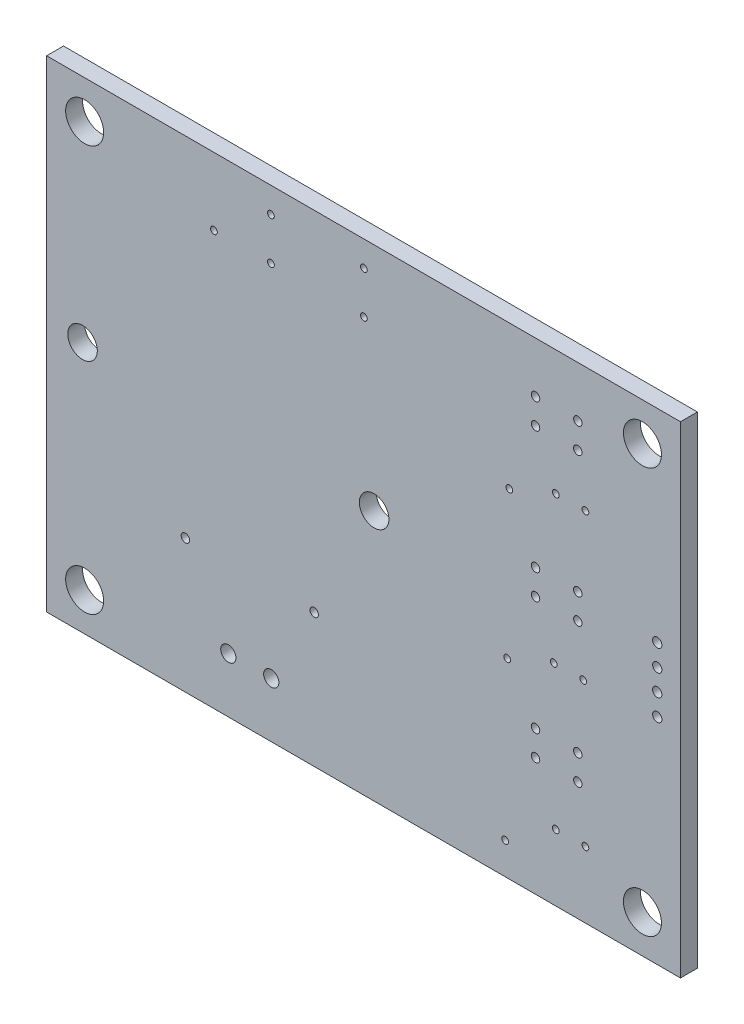
SolidWorks part; units mm, degrees
ref_plane "Спереди" through (0, 0, 0) normal (0, 0, 1) x (1, 0, 0)
ref_plane "Сверху" through (0, 0, 0) normal (0, 1, 0) x (1, 0, 0)
ref_plane "Справа" through (0, 0, 0) normal (1, 0, 0) x (0, 0, -1)
sketch "Эскиз1" plane through (0, 0, 0) normal (0, 0, 1) x (1, 0, 0)
  line L0 (-50.6905, 0) -> (50.2733, 0) construction
  line L1 (0, 39.9475) -> (0, -33.0636) construction
  line L2 (-16, -22) -> (-10.92, -22) construction
  line L3 (-37.5, -28.5) -> (37.5, -28.5)
  line L4 (-37.5, -28.5) -> (-37.5, 28.5)
  line L5 (-37.5, 28.5) -> (37.5, 28.5)
  line L6 (37.5, -28.5) -> (37.5, 28.5)
  line L7 (34.75, -3.12) -> (34.75, 2.3952) construction
  line L8 (-5.84, -12.7) -> (-33.6993, -12.7) construction
  circle A0 centre (-33, 24) radius 2.25
  circle A1 centre (33, 24) radius 2.25
  circle A2 centre (33, -24) radius 2.25
  circle A3 centre (-33, -24) radius 2.25
  circle A4 centre (-16, -22) radius 0.9
  circle A5 centre (-10.92, -22) radius 0.9
  circle A6 centre (34.75, -3.12) radius 0.55
  circle A7 centre (34.75, -0.58) radius 0.55
  circle A8 centre (34.75, 1.96) radius 0.55
  circle A9 centre (34.75, 4.5) radius 0.55
  circle A10 centre (-5.84, -12.7) radius 0.5
  circle A11 centre (-21.08, -12.7) radius 0.5
  circle A12 centre (-33.25, 1.25) radius 1.75
  circle A13 centre (1.25, 1.25) radius 1.75
  dimension "D3" = 4.5
  dimension "D5" = 4.5
  dimension "D8" = 1.8
  dimension "D9" = 5.08
  dimension "D10" = 1.1
  dimension "D13" = 2.54
  dimension "D14" = 2.54
  dimension "D15" = 2.54
  dimension "D16" = 1
  dimension "D20" = 3.5
  dimension "D23" = 38.75
  dimension "D24" = 29.75
  dimension "D1" = 75
  dimension "D2" = 57
  dimension "D4" = 4.5
  dimension "D6" = 6.5
  dimension "D7" = 21.5
  dimension "D11" = 72.25
  dimension "D12" = 25.38
  dimension "D17" = 15.8
  dimension "D18" = 31.66
  dimension "D19" = 16.42
  dimension "D21" = 4.25
  dimension "D22" = 29.75
extrude "Вытянуть1" add sketch "Эскиз1" along normal blind 2
sketch "Эскиз2" plane through (0, 0, 2) normal (0, 0, 1) x (1, 0, 0)
  line L0 (-37.5, -28.5) -> (37.5, -28.5) construction
  line L1 (-37.5, 28.5) -> (-37.5, -28.5) construction
  line L2 (-17.7, 20.5) -> (2.8598, 20.5) construction
  line L3 (19.3649, -20.65) -> (27.9828, -20.65) construction
  line L4 (19.3788, -3.72) -> (27.9967, -3.72) construction
  line L5 (19.4694, 13.75) -> (28.0873, 13.75) construction
  circle A0 centre (-17.7, 20.5) radius 0.4
  circle A1 centre (16.75, -24.75) radius 0.4
  circle A2 centre (17, -6) radius 0.4
  circle A3 centre (17.25, 11.5) radius 0.4
  circle A4 centre (-10.96, 20.5) radius 0.4
  circle A5 centre (0.04, 20.5) radius 0.4
  circle A6 centre (-10.96, 25.5) radius 0.4
  circle A7 centre (0.04, 25.5) radius 0.4
  circle A8 centre (22.75, -20.65) radius 0.4
  circle A9 centre (26.25, -20.65) radius 0.4
  circle A10 centre (22.5, -3.72) radius 0.4
  circle A11 centre (26, -3.72) radius 0.4
  circle A12 centre (22.75, 13.75) radius 0.4
  circle A13 centre (26.25, 13.75) radius 0.4
  dimension "D1" = 0.8
  dimension "D4" = 3.75
  dimension "D12" = 5
  dimension "D13" = 5
  dimension "D14" = 0.8
  dimension "D16" = 11
  dimension "D17" = 3.5
  dimension "D18" = 0.8
  dimension "D23" = 3.5
  dimension "D24" = 3.5
  dimension "D25" = 0.8
  dimension "D27" = 60.25
  dimension "D2" = 49
  dimension "D3" = 19.8
  dimension "D5" = 54.25
  dimension "D6" = 54.5
  dimension "D7" = 22.5
  dimension "D8" = 40
  dimension "D9" = 54.75
  dimension "D10" = 26.54
  dimension "D11" = 37.54
  dimension "D15" = 26.54
  dimension "D19" = 7.85
  dimension "D20" = 60.25
  dimension "D21" = 24.78
  dimension "D22" = 42.25
  dimension "D26" = 60
extrude "Вырез-Вытянуть1" cut sketch "Эскиз2" against normal blind 2
sketch "Эскиз3" plane through (0, 0, 2) normal (0, 0, 1) x (1, 0, 0)
  line L1 (-37.5, 28.5) -> (-37.5, -28.5) construction
  line L2 (-37.5, -28.5) -> (37.5, -28.5) construction
  circle A0 centre (20.35, 19.5) radius 0.5
  circle A1 centre (25.35, 19.5) radius 0.5
  circle A2 centre (25.35, 22.5) radius 0.5
  circle A3 centre (20.35, 22.5) radius 0.5
  circle A4 centre (20.35, 2) radius 0.5
  circle A5 centre (25.35, 2) radius 0.5
  circle A6 centre (25.35, 5) radius 0.5
  circle A7 centre (20.35, 5) radius 0.5
  circle A8 centre (20.35, -14.5) radius 0.5
  circle A9 centre (25.35, -14.5) radius 0.5
  circle A10 centre (25.35, -11.5) radius 0.5
  circle A11 centre (20.35, -11.5) radius 0.5
  dimension "D1" = 3
  dimension "D2" = 5
  dimension "D3" = 5
  dimension "D4" = 3
  dimension "D5" = 1
  dimension "D10" = 1
  dimension "D15" = 1
  dimension "D18" = 57.85
  dimension "D16" = 30.5
  dimension "D6" = 3
  dimension "D7" = 5
  dimension "D8" = 5
  dimension "D9" = 3
  dimension "D11" = 3
  dimension "D12" = 5
  dimension "D13" = 5
  dimension "D14" = 3
  dimension "D17" = 57.85
  dimension "D19" = 57.85
  dimension "D20" = 14
  dimension "D21" = 48
extrude "Вырез-Вытянуть2" cut sketch "Эскиз3" against normal blind 2
